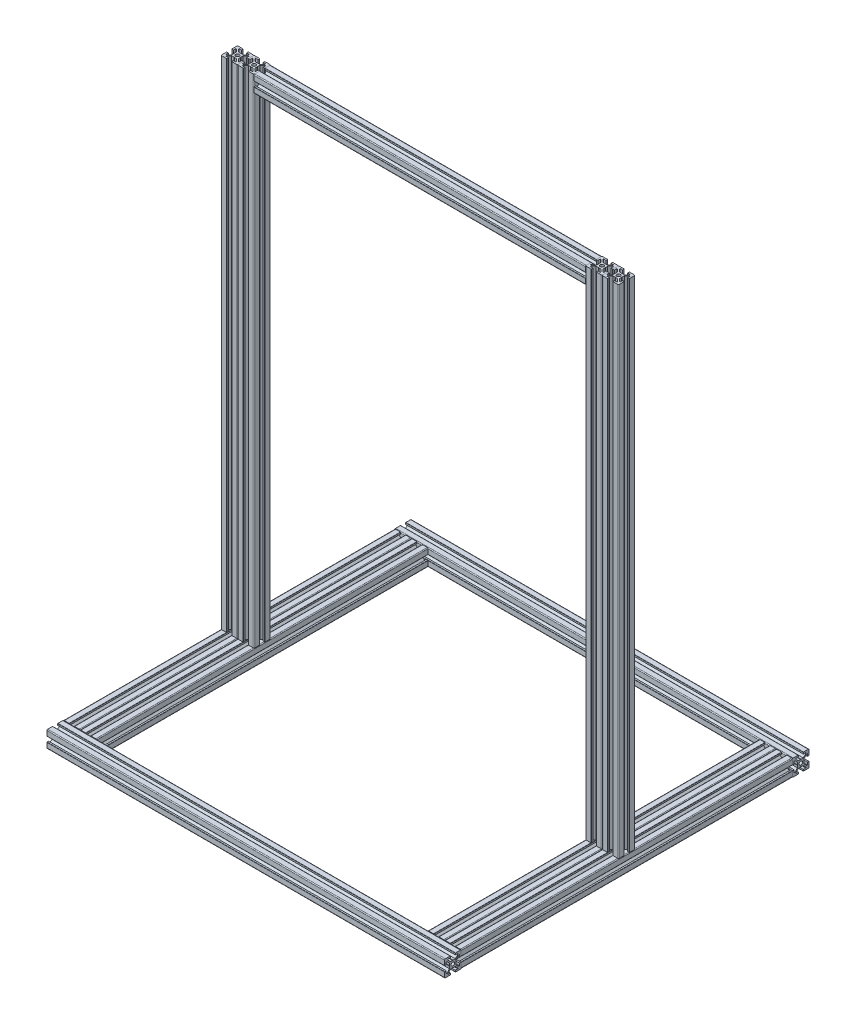
SolidWorks part; units mm, degrees
ref_plane "Front Plane" through (0, 0, 0) normal (0, 0, 1) x (1, 0, 0)
ref_plane "Top Plane" through (0, 0, 0) normal (0, 1, 0) x (1, 0, 0)
ref_plane "Right Plane" through (0, 0, 0) normal (1, 0, 0) x (0, 0, -1)
sketch "Sketch1" plane through (0, 0, 0) normal (0, 1, 0) x (1, 0, 0)
  line L0 (10, 410) -> (10, 10)
  line L1 (0, 0) -> (480, 0)
  line L3 (0, 420) -> (480, 420)
  line L5 (470, 410) -> (470, 10)
  line L6 (30, 410) -> (30, 10)
  line L7 (450, 410) -> (450, 10)
  point P13 (0, 0)
  point P14 (0, 0)
  point P15 (0, 0)
  point P16 (0, 0)
  dimension "D1" = 480
  dimension "D2" = 10
  dimension "D3" = 10
  dimension "D4" = 10
  dimension "D5" = 420
  dimension "D6" = 10
  dimension "D7" = 10
  dimension "D8" = 10
  dimension "D9" = 10
  dimension "D10" = 20
  dimension "D11" = 20
other "Sff-204t SFF-204T(2)"
ref_plane "Plane3" through (0, 0, 0) normal (1, 0, 0) x (0, 0, -1)
sketch "Sketch13" plane through (0, 0, 0) normal (1, 0, 0) x (0, 0, -1)
  line L0 (0, 3.7) -> (0, 0) construction
  line L1 (0, 3.7) -> (0.3, 4)
  line L2 (0.3, 4) -> (2.94, 4)
  line L3 (2.94, 4) -> (6, 7.06)
  line L4 (6, 7.06) -> (6, 8)
  line L5 (6, 8) -> (3, 8)
  line L6 (3, 8) -> (3, 9.7)
  line L7 (3.3, 10) -> (9, 10)
  line L8 (10, 9) -> (10, 3.3)
  line L9 (9.7, 3) -> (8, 3)
  line L10 (8, 3) -> (8, 6)
  line L11 (8, 6) -> (7.06, 6)
  line L12 (7.06, 6) -> (4, 2.94)
  line L13 (4, 2.94) -> (4, 0.3)
  line L14 (4, 0.3) -> (3.7, 0)
  line L15 (3.7, 0) -> (0, 0) construction
  line L16 (3.7, 0) -> (4, -0.3)
  line L17 (4, -0.3) -> (4, -2.94)
  line L18 (4, -2.94) -> (7.06, -6)
  line L19 (7.06, -6) -> (8, -6)
  line L20 (8, -6) -> (8, -3)
  line L21 (8, -3) -> (9.7, -3)
  line L22 (10, -3.3) -> (10, -9)
  line L23 (9, -10) -> (3.3, -10)
  line L24 (3, -9.7) -> (3, -8)
  line L25 (3, -8) -> (6, -8)
  line L26 (6, -8) -> (6, -7.06)
  line L27 (6, -7.06) -> (2.94, -4)
  line L28 (2.94, -4) -> (0.3, -4)
  line L29 (0.3, -4) -> (0, -3.7)
  line L30 (3.7, 0) -> (0, 0) construction
  line L31 (0, -3.7) -> (0, 0) construction
  line L32 (0, -3.7) -> (-0.3, -4)
  line L33 (-0.3, -4) -> (-2.94, -4)
  line L34 (-2.94, -4) -> (-6, -7.06)
  line L35 (-6, -7.06) -> (-6, -8)
  line L36 (-6, -8) -> (-3, -8)
  line L37 (-3, -8) -> (-3, -9.7)
  line L38 (-3.3, -10) -> (-9, -10)
  line L39 (-10, -9) -> (-10, -3.3)
  line L40 (-9.7, -3) -> (-8, -3)
  line L41 (-8, -3) -> (-8, -6)
  line L42 (-8, -6) -> (-7.06, -6)
  line L43 (-7.06, -6) -> (-4, -2.94)
  line L44 (-4, -2.94) -> (-4, -0.3)
  line L45 (-4, -0.3) -> (-3.7, 0)
  line L46 (0, -3.7) -> (0, 0) construction
  line L47 (-3.7, 0) -> (0, 0) construction
  line L48 (-3.7, 0) -> (-4, 0.3)
  line L49 (-4, 0.3) -> (-4, 2.94)
  line L50 (-4, 2.94) -> (-7.06, 6)
  line L51 (-7.06, 6) -> (-8, 6)
  line L52 (-8, 6) -> (-8, 3)
  line L53 (-8, 3) -> (-9.7, 3)
  line L54 (-10, 3.3) -> (-10, 9)
  line L55 (-9, 10) -> (-3.3, 10)
  line L56 (-3, 9.7) -> (-3, 8)
  line L57 (-3, 8) -> (-6, 8)
  line L58 (-6, 8) -> (-6, 7.06)
  line L59 (-6, 7.06) -> (-2.94, 4)
  line L60 (-2.94, 4) -> (-0.3, 4)
  line L61 (-0.3, 4) -> (0, 3.7)
  line L62 (-3.7, 0) -> (0, 0) construction
  line L63 (0, 3.7) -> (0, 0) construction
  circle A0 centre (0, 0) radius 2.1
  arc A1 (3, 9.7) -> (3.3, 10) centre (3.3, 9.7) cw
  arc A2 (9, 10) -> (10, 9) centre (9, 9) cw
  arc A3 (10, 3.3) -> (9.7, 3) centre (9.7, 3.3) cw
  arc A4 (9.7, -3) -> (10, -3.3) centre (9.7, -3.3) cw
  arc A5 (10, -9) -> (9, -10) centre (9, -9) cw
  arc A6 (3.3, -10) -> (3, -9.7) centre (3.3, -9.7) cw
  arc A7 (-3, -9.7) -> (-3.3, -10) centre (-3.3, -9.7) cw
  arc A8 (-9, -10) -> (-10, -9) centre (-9, -9) cw
  arc A9 (-10, -3.3) -> (-9.7, -3) centre (-9.7, -3.3) cw
  arc A10 (-9.7, 3) -> (-10, 3.3) centre (-9.7, 3.3) cw
  arc A11 (-10, 9) -> (-9, 10) centre (-9, 9) cw
  arc A12 (-3.3, 10) -> (-3, 9.7) centre (-3.3, 9.7) cw
  point P6 (0, 0)
  point P26 (0, 0)
  point P27 (0, 0)
  point P51 (0, 0)
  point P73 (0, 0)
  point P93 (0, 0)
  dimension "D1" = 4.2
  dimension "D11" = 0.3
  dimension "D12" = 0.3
  dimension "D13" = 1
  dimension "D2" = 3.7
  dimension "D3" = 4
  dimension "D4" = 0.3
  dimension "D5" = 2.64
  dimension "D6" = 3.06
  dimension "D7" = 0.94
  dimension "D8" = 3
  dimension "D9" = 2
  dimension "D10" = 2
other "Sff-204t SFF-204T(3)"
ref_plane "Plane4" through (10, 0, -410) normal (0, 0, 1) x (1, 0, 0)
sketch "Sketch14" plane through (10, 0, -410) normal (0, 0, 1) x (1, 0, 0)
  line L0 (0, 3.7) -> (0, 0) construction
  line L1 (0, 3.7) -> (0.3, 4)
  line L2 (0.3, 4) -> (2.94, 4)
  line L3 (2.94, 4) -> (6, 7.06)
  line L4 (6, 7.06) -> (6, 8)
  line L5 (6, 8) -> (3, 8)
  line L6 (3, 8) -> (3, 9.7)
  line L7 (3.3, 10) -> (9, 10)
  line L8 (10, 9) -> (10, 3.3)
  line L9 (9.7, 3) -> (8, 3)
  line L10 (8, 3) -> (8, 6)
  line L11 (8, 6) -> (7.06, 6)
  line L12 (7.06, 6) -> (4, 2.94)
  line L13 (4, 2.94) -> (4, 0.3)
  line L14 (4, 0.3) -> (3.7, 0)
  line L15 (3.7, 0) -> (0, 0) construction
  line L16 (3.7, 0) -> (4, -0.3)
  line L17 (4, -0.3) -> (4, -2.94)
  line L18 (4, -2.94) -> (7.06, -6)
  line L19 (7.06, -6) -> (8, -6)
  line L20 (8, -6) -> (8, -3)
  line L21 (8, -3) -> (9.7, -3)
  line L22 (10, -3.3) -> (10, -9)
  line L23 (9, -10) -> (3.3, -10)
  line L24 (3, -9.7) -> (3, -8)
  line L25 (3, -8) -> (6, -8)
  line L26 (6, -8) -> (6, -7.06)
  line L27 (6, -7.06) -> (2.94, -4)
  line L28 (2.94, -4) -> (0.3, -4)
  line L29 (0.3, -4) -> (0, -3.7)
  line L30 (3.7, 0) -> (0, 0) construction
  line L31 (0, -3.7) -> (0, 0) construction
  line L32 (0, -3.7) -> (-0.3, -4)
  line L33 (-0.3, -4) -> (-2.94, -4)
  line L34 (-2.94, -4) -> (-6, -7.06)
  line L35 (-6, -7.06) -> (-6, -8)
  line L36 (-6, -8) -> (-3, -8)
  line L37 (-3, -8) -> (-3, -9.7)
  line L38 (-3.3, -10) -> (-9, -10)
  line L39 (-10, -9) -> (-10, -3.3)
  line L40 (-9.7, -3) -> (-8, -3)
  line L41 (-8, -3) -> (-8, -6)
  line L42 (-8, -6) -> (-7.06, -6)
  line L43 (-7.06, -6) -> (-4, -2.94)
  line L44 (-4, -2.94) -> (-4, -0.3)
  line L45 (-4, -0.3) -> (-3.7, 0)
  line L46 (0, -3.7) -> (0, 0) construction
  line L47 (-3.7, 0) -> (0, 0) construction
  line L48 (-3.7, 0) -> (-4, 0.3)
  line L49 (-4, 0.3) -> (-4, 2.94)
  line L50 (-4, 2.94) -> (-7.06, 6)
  line L51 (-7.06, 6) -> (-8, 6)
  line L52 (-8, 6) -> (-8, 3)
  line L53 (-8, 3) -> (-9.7, 3)
  line L54 (-10, 3.3) -> (-10, 9)
  line L55 (-9, 10) -> (-3.3, 10)
  line L56 (-3, 9.7) -> (-3, 8)
  line L57 (-3, 8) -> (-6, 8)
  line L58 (-6, 8) -> (-6, 7.06)
  line L59 (-6, 7.06) -> (-2.94, 4)
  line L60 (-2.94, 4) -> (-0.3, 4)
  line L61 (-0.3, 4) -> (0, 3.7)
  line L62 (-3.7, 0) -> (0, 0) construction
  line L63 (0, 3.7) -> (0, 0) construction
  circle A0 centre (0, 0) radius 2.1
  arc A1 (3, 9.7) -> (3.3, 10) centre (3.3, 9.7) cw
  arc A2 (9, 10) -> (10, 9) centre (9, 9) cw
  arc A3 (10, 3.3) -> (9.7, 3) centre (9.7, 3.3) cw
  arc A4 (9.7, -3) -> (10, -3.3) centre (9.7, -3.3) cw
  arc A5 (10, -9) -> (9, -10) centre (9, -9) cw
  arc A6 (3.3, -10) -> (3, -9.7) centre (3.3, -9.7) cw
  arc A7 (-3, -9.7) -> (-3.3, -10) centre (-3.3, -9.7) cw
  arc A8 (-9, -10) -> (-10, -9) centre (-9, -9) cw
  arc A9 (-10, -3.3) -> (-9.7, -3) centre (-9.7, -3.3) cw
  arc A10 (-9.7, 3) -> (-10, 3.3) centre (-9.7, 3.3) cw
  arc A11 (-10, 9) -> (-9, 10) centre (-9, 9) cw
  arc A12 (-3.3, 10) -> (-3, 9.7) centre (-3.3, 9.7) cw
  point P6 (0, 0)
  point P26 (0, 0)
  point P27 (0, 0)
  point P51 (0, 0)
  point P73 (0, 0)
  point P93 (0, 0)
  dimension "D1" = 4.2
  dimension "D11" = 0.3
  dimension "D12" = 0.3
  dimension "D13" = 1
  dimension "D2" = 3.7
  dimension "D3" = 4
  dimension "D4" = 0.3
  dimension "D5" = 2.64
  dimension "D6" = 3.06
  dimension "D7" = 0.94
  dimension "D8" = 3
  dimension "D9" = 2
  dimension "D10" = 2
ref_plane "Plane5" through (0, 0, -210) normal (0, 0, 1) x (1, 0, 0)
sketch "Sketch15" plane through (0, 0, -210) normal (0, 0, 1) x (1, 0, 0)
  line L0 (10, 10) -> (10, 610)
  line L1 (40, 600) -> (440, 600)
  line L2 (470, 610) -> (470, 10)
  line L3 (30, 10) -> (30, 610)
  line L4 (450, 10) -> (450, 610)
  line L5 (6.7, 10) -> (1, 10) construction
  point P10 (0, 0)
  point P13 (480, 9)
  point P14 (0, 0)
  point P15 (0, 0)
  point P18 (0, 0)
  dimension "D1" = 10
  dimension "D2" = 20
  dimension "D3" = 20
  dimension "D4" = 10
  dimension "D5" = 600
  dimension "D6" = 400
  dimension "D7" = 10
  dimension "D8" = 10
other "Sff-204t SFF-204T(5)"
ref_plane "Plane6" through (10, 10, -210) normal (0, 1, 0) x (-1, 0, 0)
sketch "Sketch16" plane through (10, 10, -210) normal (0, 1, 0) x (-1, 0, 0)
  line L0 (0, 3.7) -> (0, 0) construction
  line L1 (0, 3.7) -> (0.3, 4)
  line L2 (0.3, 4) -> (2.94, 4)
  line L3 (2.94, 4) -> (6, 7.06)
  line L4 (6, 7.06) -> (6, 8)
  line L5 (6, 8) -> (3, 8)
  line L6 (3, 8) -> (3, 9.7)
  line L7 (3.3, 10) -> (9, 10)
  line L8 (10, 9) -> (10, 3.3)
  line L9 (9.7, 3) -> (8, 3)
  line L10 (8, 3) -> (8, 6)
  line L11 (8, 6) -> (7.06, 6)
  line L12 (7.06, 6) -> (4, 2.94)
  line L13 (4, 2.94) -> (4, 0.3)
  line L14 (4, 0.3) -> (3.7, 0)
  line L15 (3.7, 0) -> (0, 0) construction
  line L16 (3.7, 0) -> (4, -0.3)
  line L17 (4, -0.3) -> (4, -2.94)
  line L18 (4, -2.94) -> (7.06, -6)
  line L19 (7.06, -6) -> (8, -6)
  line L20 (8, -6) -> (8, -3)
  line L21 (8, -3) -> (9.7, -3)
  line L22 (10, -3.3) -> (10, -9)
  line L23 (9, -10) -> (3.3, -10)
  line L24 (3, -9.7) -> (3, -8)
  line L25 (3, -8) -> (6, -8)
  line L26 (6, -8) -> (6, -7.06)
  line L27 (6, -7.06) -> (2.94, -4)
  line L28 (2.94, -4) -> (0.3, -4)
  line L29 (0.3, -4) -> (0, -3.7)
  line L30 (3.7, 0) -> (0, 0) construction
  line L31 (0, -3.7) -> (0, 0) construction
  line L32 (0, -3.7) -> (-0.3, -4)
  line L33 (-0.3, -4) -> (-2.94, -4)
  line L34 (-2.94, -4) -> (-6, -7.06)
  line L35 (-6, -7.06) -> (-6, -8)
  line L36 (-6, -8) -> (-3, -8)
  line L37 (-3, -8) -> (-3, -9.7)
  line L38 (-3.3, -10) -> (-9, -10)
  line L39 (-10, -9) -> (-10, -3.3)
  line L40 (-9.7, -3) -> (-8, -3)
  line L41 (-8, -3) -> (-8, -6)
  line L42 (-8, -6) -> (-7.06, -6)
  line L43 (-7.06, -6) -> (-4, -2.94)
  line L44 (-4, -2.94) -> (-4, -0.3)
  line L45 (-4, -0.3) -> (-3.7, 0)
  line L46 (0, -3.7) -> (0, 0) construction
  line L47 (-3.7, 0) -> (0, 0) construction
  line L48 (-3.7, 0) -> (-4, 0.3)
  line L49 (-4, 0.3) -> (-4, 2.94)
  line L50 (-4, 2.94) -> (-7.06, 6)
  line L51 (-7.06, 6) -> (-8, 6)
  line L52 (-8, 6) -> (-8, 3)
  line L53 (-8, 3) -> (-9.7, 3)
  line L54 (-10, 3.3) -> (-10, 9)
  line L55 (-9, 10) -> (-3.3, 10)
  line L56 (-3, 9.7) -> (-3, 8)
  line L57 (-3, 8) -> (-6, 8)
  line L58 (-6, 8) -> (-6, 7.06)
  line L59 (-6, 7.06) -> (-2.94, 4)
  line L60 (-2.94, 4) -> (-0.3, 4)
  line L61 (-0.3, 4) -> (0, 3.7)
  line L62 (-3.7, 0) -> (0, 0) construction
  line L63 (0, 3.7) -> (0, 0) construction
  circle A0 centre (0, 0) radius 2.1
  arc A1 (3, 9.7) -> (3.3, 10) centre (3.3, 9.7) cw
  arc A2 (9, 10) -> (10, 9) centre (9, 9) cw
  arc A3 (10, 3.3) -> (9.7, 3) centre (9.7, 3.3) cw
  arc A4 (9.7, -3) -> (10, -3.3) centre (9.7, -3.3) cw
  arc A5 (10, -9) -> (9, -10) centre (9, -9) cw
  arc A6 (3.3, -10) -> (3, -9.7) centre (3.3, -9.7) cw
  arc A7 (-3, -9.7) -> (-3.3, -10) centre (-3.3, -9.7) cw
  arc A8 (-9, -10) -> (-10, -9) centre (-9, -9) cw
  arc A9 (-10, -3.3) -> (-9.7, -3) centre (-9.7, -3.3) cw
  arc A10 (-9.7, 3) -> (-10, 3.3) centre (-9.7, 3.3) cw
  arc A11 (-10, 9) -> (-9, 10) centre (-9, 9) cw
  arc A12 (-3.3, 10) -> (-3, 9.7) centre (-3.3, 9.7) cw
  point P6 (0, 0)
  point P26 (0, 0)
  point P27 (0, 0)
  point P51 (0, 0)
  point P73 (0, 0)
  point P93 (0, 0)
  dimension "D1" = 4.2
  dimension "D11" = 0.3
  dimension "D12" = 0.3
  dimension "D13" = 1
  dimension "D2" = 3.7
  dimension "D3" = 4
  dimension "D4" = 0.3
  dimension "D5" = 2.64
  dimension "D6" = 3.06
  dimension "D7" = 0.94
  dimension "D8" = 3
  dimension "D9" = 2
  dimension "D10" = 2
other "Sff-204t SFF-204T(6)"
ref_plane "Plane7" through (40, 600, -210) normal (1, 0, 0) x (0, 1, 0)
sketch "Sketch17" plane through (40, 600, -210) normal (1, 0, 0) x (0, 1, 0)
  line L0 (0, 3.7) -> (0, 0) construction
  line L1 (0, 3.7) -> (0.3, 4)
  line L2 (0.3, 4) -> (2.94, 4)
  line L3 (2.94, 4) -> (6, 7.06)
  line L4 (6, 7.06) -> (6, 8)
  line L5 (6, 8) -> (3, 8)
  line L6 (3, 8) -> (3, 9.7)
  line L7 (3.3, 10) -> (9, 10)
  line L8 (10, 9) -> (10, 3.3)
  line L9 (9.7, 3) -> (8, 3)
  line L10 (8, 3) -> (8, 6)
  line L11 (8, 6) -> (7.06, 6)
  line L12 (7.06, 6) -> (4, 2.94)
  line L13 (4, 2.94) -> (4, 0.3)
  line L14 (4, 0.3) -> (3.7, 0)
  line L15 (3.7, 0) -> (0, 0) construction
  line L16 (3.7, 0) -> (4, -0.3)
  line L17 (4, -0.3) -> (4, -2.94)
  line L18 (4, -2.94) -> (7.06, -6)
  line L19 (7.06, -6) -> (8, -6)
  line L20 (8, -6) -> (8, -3)
  line L21 (8, -3) -> (9.7, -3)
  line L22 (10, -3.3) -> (10, -9)
  line L23 (9, -10) -> (3.3, -10)
  line L24 (3, -9.7) -> (3, -8)
  line L25 (3, -8) -> (6, -8)
  line L26 (6, -8) -> (6, -7.06)
  line L27 (6, -7.06) -> (2.94, -4)
  line L28 (2.94, -4) -> (0.3, -4)
  line L29 (0.3, -4) -> (0, -3.7)
  line L30 (3.7, 0) -> (0, 0) construction
  line L31 (0, -3.7) -> (0, 0) construction
  line L32 (0, -3.7) -> (-0.3, -4)
  line L33 (-0.3, -4) -> (-2.94, -4)
  line L34 (-2.94, -4) -> (-6, -7.06)
  line L35 (-6, -7.06) -> (-6, -8)
  line L36 (-6, -8) -> (-3, -8)
  line L37 (-3, -8) -> (-3, -9.7)
  line L38 (-3.3, -10) -> (-9, -10)
  line L39 (-10, -9) -> (-10, -3.3)
  line L40 (-9.7, -3) -> (-8, -3)
  line L41 (-8, -3) -> (-8, -6)
  line L42 (-8, -6) -> (-7.06, -6)
  line L43 (-7.06, -6) -> (-4, -2.94)
  line L44 (-4, -2.94) -> (-4, -0.3)
  line L45 (-4, -0.3) -> (-3.7, 0)
  line L46 (0, -3.7) -> (0, 0) construction
  line L47 (-3.7, 0) -> (0, 0) construction
  line L48 (-3.7, 0) -> (-4, 0.3)
  line L49 (-4, 0.3) -> (-4, 2.94)
  line L50 (-4, 2.94) -> (-7.06, 6)
  line L51 (-7.06, 6) -> (-8, 6)
  line L52 (-8, 6) -> (-8, 3)
  line L53 (-8, 3) -> (-9.7, 3)
  line L54 (-10, 3.3) -> (-10, 9)
  line L55 (-9, 10) -> (-3.3, 10)
  line L56 (-3, 9.7) -> (-3, 8)
  line L57 (-3, 8) -> (-6, 8)
  line L58 (-6, 8) -> (-6, 7.06)
  line L59 (-6, 7.06) -> (-2.94, 4)
  line L60 (-2.94, 4) -> (-0.3, 4)
  line L61 (-0.3, 4) -> (0, 3.7)
  line L62 (-3.7, 0) -> (0, 0) construction
  line L63 (0, 3.7) -> (0, 0) construction
  circle A0 centre (0, 0) radius 2.1
  arc A1 (3, 9.7) -> (3.3, 10) centre (3.3, 9.7) cw
  arc A2 (9, 10) -> (10, 9) centre (9, 9) cw
  arc A3 (10, 3.3) -> (9.7, 3) centre (9.7, 3.3) cw
  arc A4 (9.7, -3) -> (10, -3.3) centre (9.7, -3.3) cw
  arc A5 (10, -9) -> (9, -10) centre (9, -9) cw
  arc A6 (3.3, -10) -> (3, -9.7) centre (3.3, -9.7) cw
  arc A7 (-3, -9.7) -> (-3.3, -10) centre (-3.3, -9.7) cw
  arc A8 (-9, -10) -> (-10, -9) centre (-9, -9) cw
  arc A9 (-10, -3.3) -> (-9.7, -3) centre (-9.7, -3.3) cw
  arc A10 (-9.7, 3) -> (-10, 3.3) centre (-9.7, 3.3) cw
  arc A11 (-10, 9) -> (-9, 10) centre (-9, 9) cw
  arc A12 (-3.3, 10) -> (-3, 9.7) centre (-3.3, 9.7) cw
  point P6 (0, 0)
  point P26 (0, 0)
  point P27 (0, 0)
  point P51 (0, 0)
  point P73 (0, 0)
  point P93 (0, 0)
  dimension "D1" = 4.2
  dimension "D11" = 0.3
  dimension "D12" = 0.3
  dimension "D13" = 1
  dimension "D2" = 3.7
  dimension "D3" = 4
  dimension "D4" = 0.3
  dimension "D5" = 2.64
  dimension "D6" = 3.06
  dimension "D7" = 0.94
  dimension "D8" = 3
  dimension "D9" = 2
  dimension "D10" = 2
